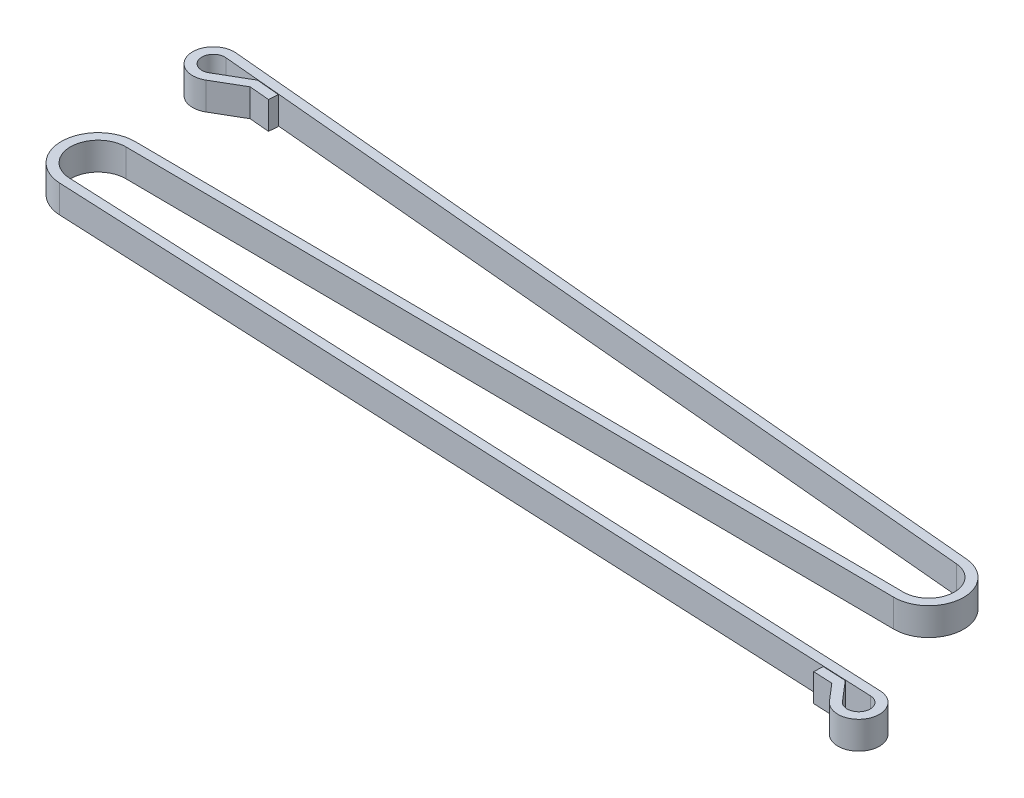
SolidWorks part; units mm, degrees
ref_plane "Front Plane" through (0, 0, 0) normal (0, 0, 1) x (1, 0, 0)
ref_plane "Top Plane" through (0, 0, 0) normal (0, 1, 0) x (1, 0, 0)
ref_plane "Right Plane" through (0, 0, 0) normal (1, 0, 0) x (0, 0, -1)
sketch "Sketch2" plane through (0, 19.3268, 0) normal (0, 1, 0) x (1, 0, 0)
  line L0 (-94.8481, 22.839) -> (-88.2219, 26.6933)
  line L1 (-88.2219, 26.6933) -> (-83.2425, 26.2406)
  line L2 (78.5025, 11.6372) -> (-95.8788, 27.4897)
  line L3 (77.956, 0.5602) -> (-89.9366, 1.8897)
  line L4 (94.0087, -22.5026) -> (-90.3641, -14.1017)
  line L5 (91.9973, -26.6276) -> (88.3229, -22.3436)
  line L6 (88.3229, -22.3436) -> (83.3281, -22.116)
  circle A0 centre (-96.1051, 25) radius 2.5 construction
  circle A1 centre (93.8949, -25) radius 2.5 construction
  circle A3 centre (78, 6.11) radius 5.55 construction
  circle A4 centre (93.8949, -25) radius 2.5 construction
  arc A5 (-89.9366, 1.8897) -> (-90.3641, -14.1017) centre (-90, -6.11) ccw
  circle A7 centre (-90, -6.11) radius 6 construction
  circle A8 centre (-96.1051, 25) radius 2.5 construction
  circle A9 centre (-90, -6.11) radius 8 construction
  arc A10 (78.5025, 11.6372) -> (77.956, 0.5602) centre (78, 6.11) cw
  arc A11 (-95.8788, 27.4897) -> (-94.8481, 22.839) centre (-96.1051, 25) ccw
  arc A12 (94.0087, -22.5026) -> (91.9973, -26.6276) centre (93.8949, -25) cw
  dimension "D1" = 0.1
  dimension "D2" = 0.1
  dimension "D3" = 5
  dimension "D4" = 5
extrude "Extrude-Thin1" add sketch "Sketch2" along normal mid plane 6 thin
